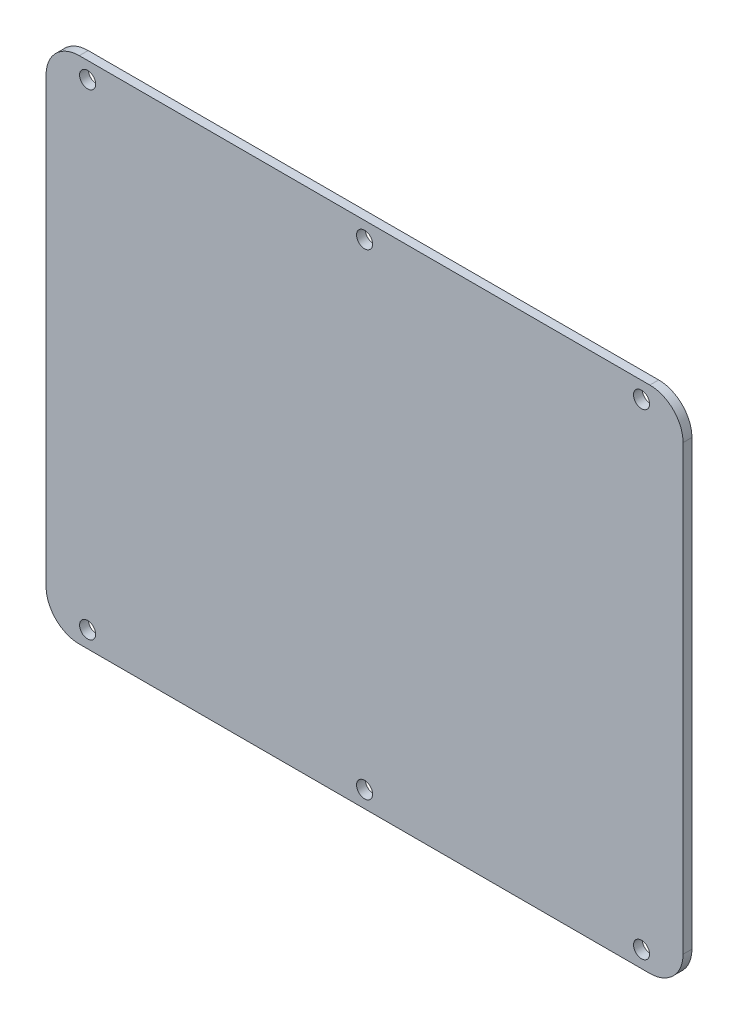
SolidWorks part; units mm, degrees
ref_plane "Front" through (0, 0, 0) normal (0, 0, 1) x (1, 0, 0)
ref_plane "Top" through (0, 0, 0) normal (0, 1, 0) x (1, 0, 0)
ref_plane "Right" through (0, 0, 0) normal (1, 0, 0) x (0, 0, -1)
sketch "Sketch1" plane through (0, 0, 0) normal (0, 0, 1) x (1, 0, 0)
  line L1 (-57.5, 46) -> (57.5, 46)
  line L2 (-57.5, 46) -> (-57.5, -46)
  line L3 (-57.5, -46) -> (57.5, -46)
  line L4 (57.5, 46) -> (57.5, -46)
  line L5 (-57.5, 46) -> (57.5, -46) construction
  line L6 (-57.5, -46) -> (57.5, 46) construction
  point P0 (0, 0)
  dimension "D1" = 92
  dimension "D2" = 115
extrude "Boss-Extrude1" add sketch "Sketch1" along normal blind 1.6002
hole_wizard "M2.5 Clearance Hole1" positions "Sketch2" profile "Sketch3" hole size "M2.5" standard "ANSI Metric" end condition up to next
sketch "Sketch2" plane through (0, 0, 1.6002) normal (0, 0, 1) x (1, 0, 0)
  line L1 (-50, 43) -> (50, 43)
  line L2 (-50, 43) -> (-50, -43)
  line L3 (-50, -43) -> (50, -43)
  line L4 (50, 43) -> (50, -43)
  line L5 (-50, 43) -> (50, -43) construction
  line L6 (-50, -43) -> (50, 43) construction
  line L12 (-50, 0) -> (50, 0) construction
  point P2 (50, -43)
  point P55 (-50, 43)
  point P56 (-50, -43)
  point P57 (50, 43)
  point P86 (0, 43)
  point P88 (0, -43)
  dimension "D2" = 100
  dimension "D3" = 86
sketch "Sketch3" plane through (50, -43, 1.6002) normal (1, 0, 0) x (0, -1, 0)
  line L0 (0, 0) -> (0, 1.6002)
  line L1 (0, 1.6002) -> (1.45, 1.6002)
  line L2 (1.45, 1.6002) -> (1.45, 0)
  line L5 (1.45, 0) -> (0, 0)
  line L11 (0, -6.35) -> (0, 107.95) construction
  dimension "Thru Hole Dia." = 2.9
  dimension "Thru Hole Depth" = 1.6002
fillet "Fillet2" radius 6 4 edges at (57.5, -46, 0.8001) (-57.5, -46, 0.8001) (57.5, 46, 0.8001) (-57.5, 46, 0.8001)
